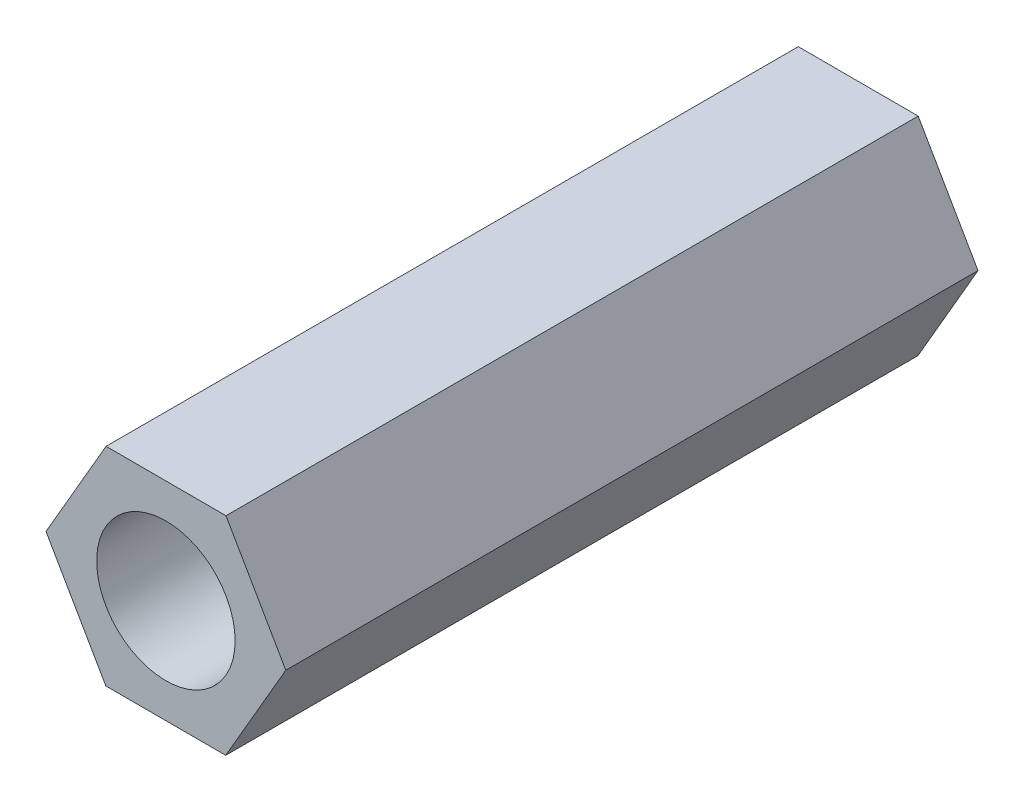
SolidWorks part; units mm, degrees
ref_plane "Front Plane" through (0, 0, 0) normal (0, 0, 1) x (1, 0, 0)
ref_plane "Top Plane" through (0, 0, 0) normal (0, 1, 0) x (1, 0, 0)
ref_plane "Right Plane" through (0, 0, 0) normal (1, 0, 0) x (0, 0, -1)
sketch "Sketch2" plane through (0, 0, 0) normal (0, 0, 1) x (1, 0, 0)
  line L1 (-1.7278, 3.0024) -> (-3.4641, 0.0049)
  line L2 (-3.4641, 0.0049) -> (-1.7363, -2.9975)
  line L3 (-1.7363, -2.9975) -> (1.7278, -3.0024)
  line L4 (1.7278, -3.0024) -> (3.4641, -0.0049)
  line L5 (3.4641, -0.0049) -> (1.7363, 2.9975)
  line L6 (1.7363, 2.9975) -> (-1.7278, 3.0024)
  circle A0 centre (0, 0) radius 3
  circle A1 centre (0, 0) radius 3 construction
  circle A2 centre (0, 0) radius 2
extrude "Boss-Extrude1" add sketch "Sketch2" along normal blind 20 contours A0 A2 | A0 L6 L1 | A0 L5 L6 | A0 L4 L5 | A0 L3 L4 | A0 L2 L3 | A0 L1 L2
